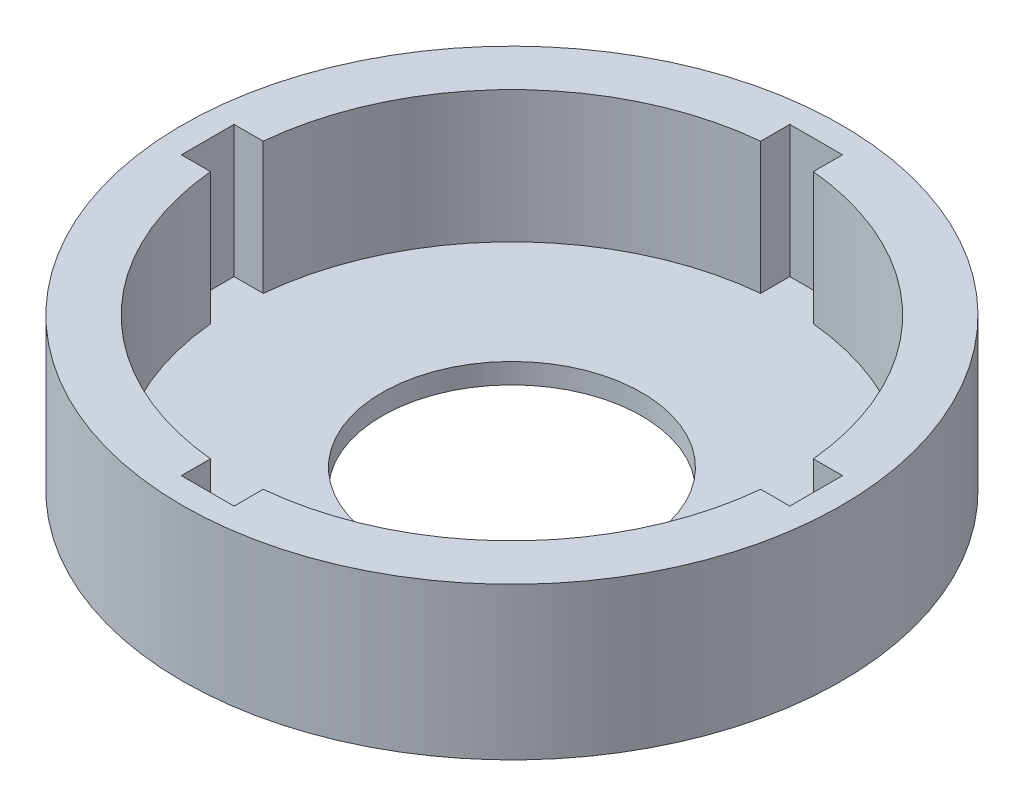
SolidWorks part; units mm, degrees
ref_plane "Front Plane" through (0, 0, 0) normal (0, 0, 1) x (1, 0, 0)
ref_plane "Top Plane" through (0, 0, 0) normal (0, 1, 0) x (1, 0, 0)
ref_plane "Right Plane" through (0, 0, 0) normal (1, 0, 0) x (0, 0, -1)
sketch "Sketch1" plane through (0, 0, 0) normal (0, 1, 0) x (1, 0, 0)
  circle A0 centre (0, 0) radius 32.5
  circle A1 centre (0, 0) radius 12.8
  dimension "D1" = 65
  dimension "D2" = 25.6
extrude "Boss-Extrude1" add sketch "Sketch1" along normal blind 2
sketch "Sketch2" plane through (0, 2, 0) normal (0, 1, 0) x (1, 0, 0)
  line L0 (0, -55) -> (0, 55) construction
  line L1 (2.6, -30) -> (-2.6, -30)
  line L2 (2.6, -30) -> (2.6, -26.0456)
  line L3 (2.6, -26.0456) -> (-2.6, -26.0456)
  line L4 (-2.6, -30) -> (-2.6, -26.0456)
  line L5 (2.6, -30) -> (-2.6, -26.0456) construction
  line L6 (2.6, -26.0456) -> (-2.6, -30) construction
  line L7 (-30, -2.6) -> (-30, 2.6)
  line L8 (-30, -2.6) -> (-26.0456, -2.6)
  line L9 (-30, 2.6) -> (-26.0456, 2.6)
  line L10 (-26.0456, -2.6) -> (-26.0456, 2.6)
  line L11 (-2.6, 30) -> (2.6, 30)
  line L12 (-2.6, 30) -> (-2.6, 26.0456)
  line L13 (2.6, 30) -> (2.6, 26.0456)
  line L14 (-2.6, 26.0456) -> (2.6, 26.0456)
  line L15 (30, 2.6) -> (30, -2.6)
  line L16 (30, 2.6) -> (26.0456, 2.6)
  line L17 (30, -2.6) -> (26.0456, -2.6)
  line L18 (26.0456, 2.6) -> (26.0456, -2.6)
  circle A0 centre (0, 0) radius 27.1
  circle A1 centre (0, 0) radius 27.25
  circle A2 centre (0, 0) radius 32.5
  point P4 (0, -28.0228)
  circle M7 centre (0, 0) radius 32.5
  dimension "D1" = 54.5
  dimension "D2" = 54.2
  dimension "D3" = 30
  dimension "D4" = 5.2
  dimension "D5" = 4
extrude "Boss-Extrude2" add sketch "Sketch2" along normal blind 13 contours A0 L2 L1 L4 L8 L7 L9 L12 L11 L13 L16 L15 L17 M7
